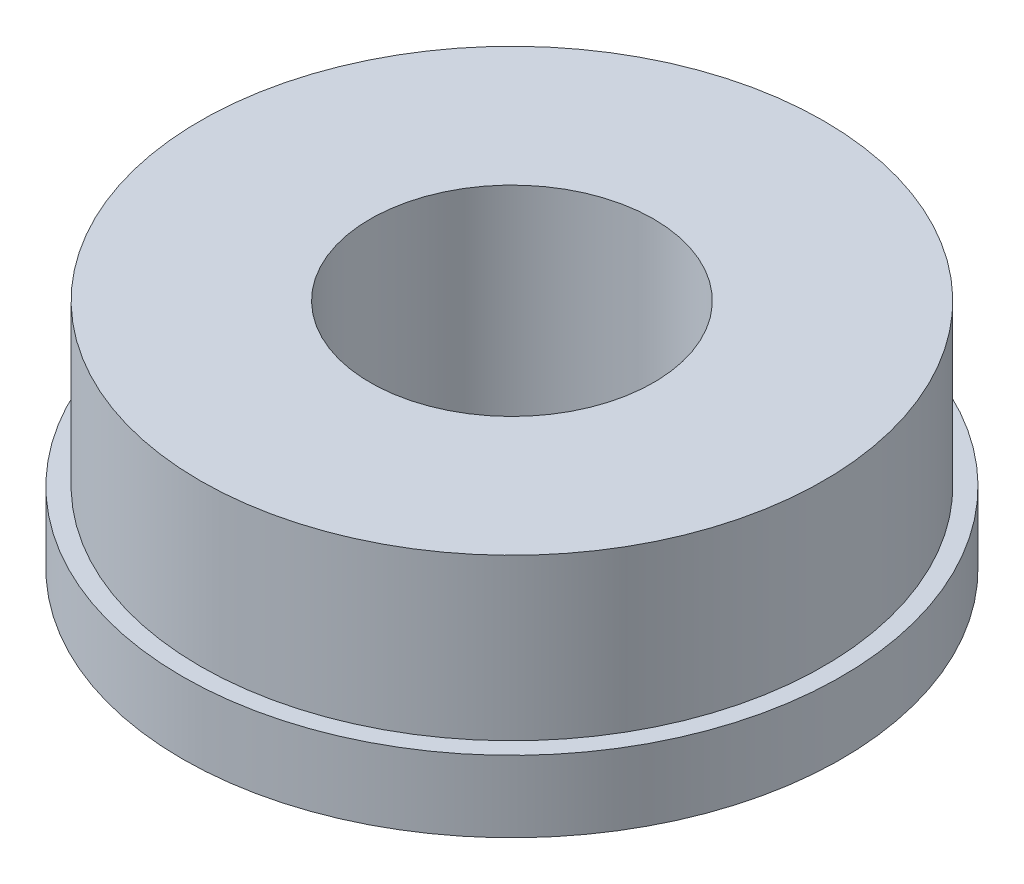
SolidWorks part; units mm, degrees
ref_plane "Front Plane" through (0, 0, 0) normal (0, 0, 1) x (1, 0, 0)
ref_plane "Top Plane" through (0, 0, 0) normal (0, 1, 0) x (1, 0, 0)
ref_plane "Right Plane" through (0, 0, 0) normal (1, 0, 0) x (0, 0, -1)
sketch "Sketch1" plane through (0, 0, 0) normal (0, 1, 0) x (1, 0, 0)
  line L0 (0, 50.2172) -> (0, 26.2726) construction
  line L1 (-8.4804, 0) -> (17.2933, 0) construction
  circle A0 centre (0, 0) radius 7.94
  circle A1 centre (0, 0) radius 17.465
  dimension "D2" = 15.88
  dimension "D1" = 34.93
extrude "Boss-Extrude1" add sketch "Sketch1" along normal blind 13
sketch "Sketch2" plane through (0, 0, 0) normal (0, 1, 0) x (1, 0, 0)
  circle A0 centre (0, 0) radius 18.465
  circle A1 centre (0, 0) radius 7.94
  dimension "D1" = 36.93
  dimension "D2" = 15.88
extrude "Boss-Extrude3" add sketch "Sketch2" along normal blind 4
equation "\"Bearing Total Height\"= 13mm"
equation "\"D1@Boss-Extrude1\"=\"Bearing Total Height\""
equation "\"Flange diameter\"= \"Bearing outside diameter\" + \"Flange thickness\""
equation "\"Flange height\"= 4mm"
equation "\"D1@Sketch2\"=\"Flange diameter\""
equation "\"D2@Sketch2\"=15.88mm"
equation "\"D1@Boss-Extrude3\"=\"Flange height\""
equation "\"Bearing inside diameter\"= 15.88mm"
equation "\"Bearing outside diameter\"= 34.93mm"
equation "\"D1@Sketch1\"=\"Bearing outside diameter\""
equation "\"D2@Sketch1\"=\"Bearing inside diameter\""
equation "\"Flange thickness\"= 2mm"
